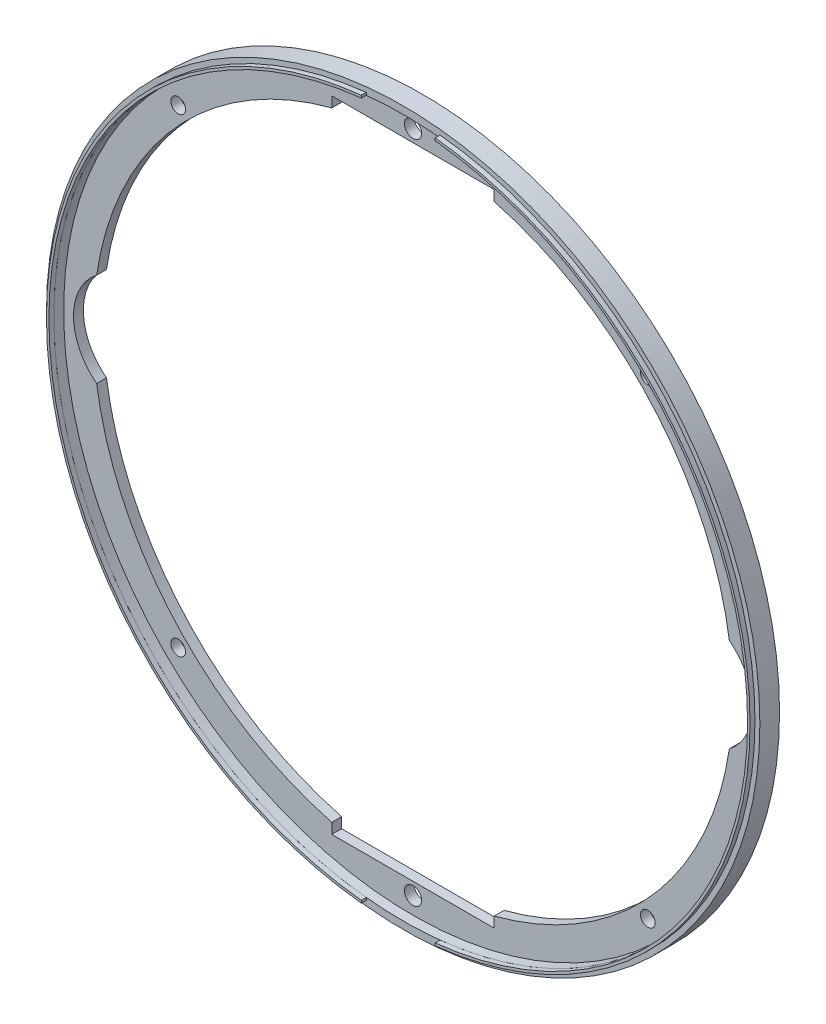
SolidWorks part; units mm, degrees
material "ABS"
ref_plane "Ebene vorne" through (0, 0, 0) normal (0, 0, 1) x (1, 0, 0)
ref_plane "Ebene oben" through (0, 0, 0) normal (0, 1, 0) x (1, 0, 0)
ref_plane "Ebene rechts" through (0, 0, 0) normal (1, 0, 0) x (0, 0, -1)
sketch "Skizze4" plane through (0, 0, 0) normal (0, 0, 1) x (1, 0, 0)
  circle A0 centre (0, 0) radius 72.5
  circle A1 centre (0, 0) radius 65
  dimension "D2" = 130
  dimension "D1" = 145
extrude "Base Ring" add sketch "Skizze4" along normal blind 2
hole_wizard "Spacer Placement" positions "Skizze5" profile "Skizze6" hole size "Ø3.5" standard "ISO" end condition through all
sketch "Skizze5" plane through (0, 0, 2) normal (0, 0, 1) x (1, 0, 0)
  line L2 (-47.7297, 47.7297) -> (-47.7297, -47.7297) construction
  line L3 (-47.7297, -47.7297) -> (47.7297, -47.7297) construction
  line L4 (47.7297, -47.7297) -> (47.7297, 47.7297) construction
  line L5 (47.7297, 47.7297) -> (-47.7297, 47.7297) construction
  circle A0 centre (0, 0) radius 47.7297 construction
  circle A3 centre (0, 0) radius 67.5 construction
  point P0 (-47.7297, 47.7297)
  point P2 (47.7297, 47.7297)
  point P4 (47.7297, -47.7297)
  point P6 (-47.7297, -47.7297)
  dimension "D1" = 135
sketch "Skizze6" plane through (-47.7297, 47.7297, 2) normal (1, 0, 0) x (0, -1, 0)
  line L0 (0, 0) -> (0, 2)
  line L1 (0, 2) -> (1.5, 2)
  line L2 (1.5, 2) -> (1.5, 0)
  line L5 (1.5, 0) -> (0, 0)
  line L11 (0, -6.35) -> (0, 107.95) construction
  dimension "Bohrerdurchmesser" = 3
  dimension "Bohrungstiefe" = 2
sketch "Skizze8" plane through (0, 0, 2) normal (0, 0, 1) x (1, 0, 0)
  circle A0 centre (57, 0) radius 12
  circle A1 centre (-57, 0) radius 12
  dimension "D1" = 57
  dimension "D3" = 24
  dimension "D2" = 57
extrude "Ball Castor" cut sketch "Skizze8" against normal through all
sketch "Skizze9" plane through (0, 0, 0) normal (0, 0, 1) x (1, 0, 0)
  line L1 (16.5, -65) -> (-16.5, -65)
  line L2 (16.5, -65) -> (16.5, 65)
  line L3 (16.5, 65) -> (-16.5, 65)
  line L4 (-16.5, -65) -> (-16.5, 65)
  line L5 (16.5, -65) -> (-16.5, 65) construction
  line L6 (16.5, 65) -> (-16.5, -65) construction
  line L7 (16.5, -50) -> (-16.5, -50)
  line L8 (16.5, -50) -> (16.5, 50)
  line L9 (16.5, 50) -> (-16.5, 50)
  line L10 (-16.5, -50) -> (-16.5, 50)
  line L11 (16.5, -50) -> (-16.5, 50) construction
  line L12 (16.5, 50) -> (-16.5, -50) construction
  point P0 (0, 0)
  point P5 (0, 0)
  dimension "D1" = 65
  dimension "D2" = 50
  dimension "D3" = 33
extrude "Wheels" cut sketch "Skizze9" along normal through all contours L1 L10 L3 L4 | L8 L1 L2 L3
sketch "Skizze11" plane through (0, 0, 2) normal (0, 0, 1) x (1, 0, 0)
  circle A0 centre (0, 0) radius 72.5
  circle A2 centre (0, 0) radius 72.5 construction
  circle A3 centre (0, 0) radius 71
  dimension "D1" = 1.5
extrude "Side Wall" add sketch "Skizze11" along normal blind 2
sketch "Skizze14" plane through (0, 0, 4) normal (0, 0, 1) x (1, 0, 0)
  circle A0 centre (0, 0) radius 71
  circle A1 centre (0, 0) radius 71.5
  circle A2 centre (0, 0) radius 71 construction
  dimension "D1" = 0.5
extrude "Inner Wall" add sketch "Skizze14" along normal blind 1 separate body contours A0 | A1
hole_wizard "Cover Screws" positions "Skizze12" profile "Skizze13" hole size "Ø3.5" standard "ISO" end condition through all
sketch "Skizze12" plane through (0, 0, 2) normal (0, 0, 1) x (1, 0, 0)
  point P0 (0, -67.5)
  point P2 (0, 67.5)
  dimension "D1" = 67.5
  dimension "D2" = 67.5
sketch "Skizze13" plane through (0, -67.5, 2) normal (1, 0, 0) x (0, -1, 0)
  line L0 (0, 0) -> (0, 2)
  line L1 (0, 2) -> (1.75, 2)
  line L2 (1.75, 2) -> (1.75, 0)
  line L5 (1.75, 0) -> (0, 0)
  line L11 (0, -6.35) -> (0, 107.95) construction
  dimension "Bohrerdurchmesser" = 3.5
  dimension "Bohrungstiefe" = 2
sketch "Skizze15" plane through (0, 0, 5) normal (0, 0, 1) x (1, 0, 0)
  line L1 (-7.5, -72.5) -> (7.5, -72.5)
  line L2 (-7.5, -72.5) -> (-7.5, 72.5)
  line L3 (-7.5, 72.5) -> (7.5, 72.5)
  line L4 (7.5, -72.5) -> (7.5, 72.5)
  line L5 (-7.5, -72.5) -> (7.5, 72.5) construction
  line L6 (-7.5, 72.5) -> (7.5, -72.5) construction
  circle A0 centre (0, 0) radius 72.5 construction
  point P0 (0, 0)
  dimension "D1" = 15
extrude "Cover Opening" cut sketch "Skizze15" against normal up to surface (1 mm away) contours L2 L1 L4 L3 up to face at (72.5, 0, 4)
equation "\"D_outer\"= 145mm"
equation "\"d_inner\"= 130mm"
equation "\"d_spacers\"= 135mm"
equation "\"d_spacer_hole\"= 3.5mm"
equation "\"D2@Skizze4\" = \"d_inner\""
equation "\"D1@Skizze4\"=\"D_outer\""
equation "\"D1@Skizze5\"=\"d_spacers\""
